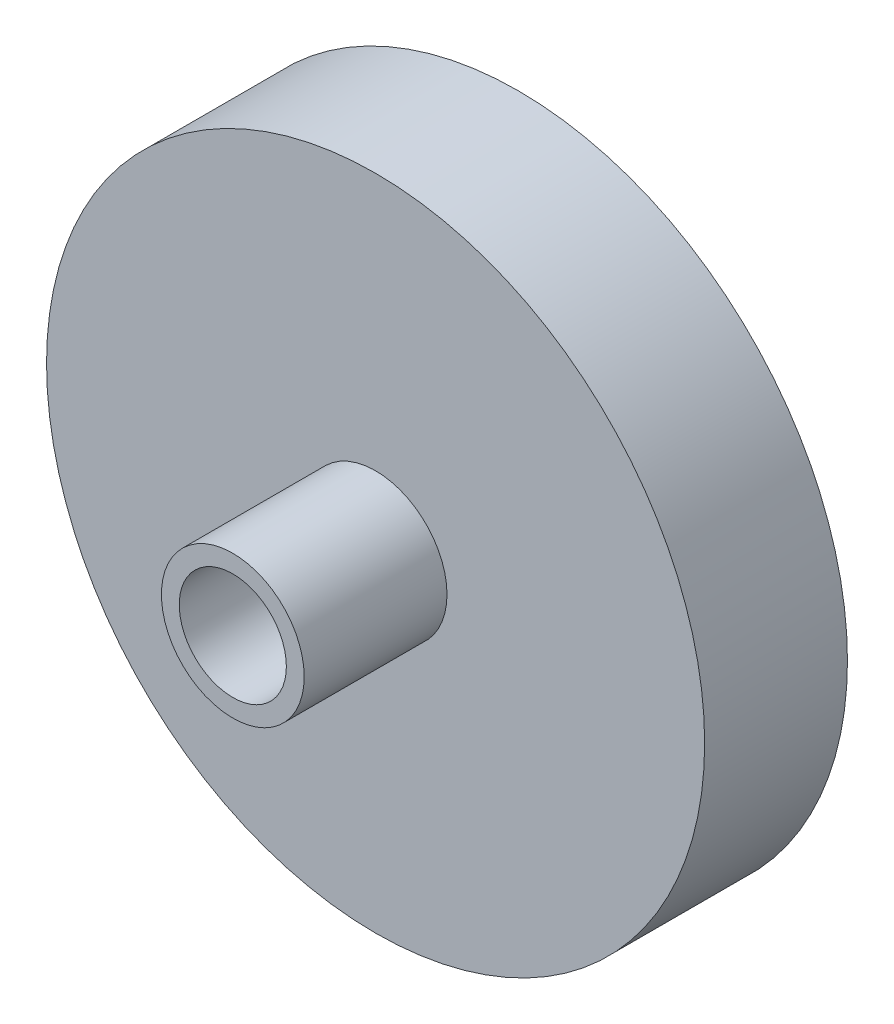
SolidWorks part; units mm, degrees
ref_plane "Plan de face" through (0, 0, 0) normal (0, 0, 1) x (1, 0, 0)
ref_plane "Plan de dessus" through (0, 0, 0) normal (0, 1, 0) x (1, 0, 0)
ref_plane "Plan de droite" through (0, 0, 0) normal (1, 0, 0) x (0, 0, -1)
sketch "Esquisse1" plane through (0, 0, 0) normal (0, 0, 1) x (1, 0, 0)
  circle A0 centre (0, 0) radius 46.0896
extrude "Boss.-Extru.1" add sketch "Esquisse1" along normal blind 20
sketch "Esquisse2" plane through (0, 0, 20) normal (0, 0, 1) x (1, 0, 0)
  circle A0 centre (0, 0) radius 10
  dimension "D1" = 20
extrude "Boss.-Extru.2" add sketch "Esquisse2" along normal blind 20
sketch "Esquisse3" plane through (0, 0, 40) normal (0, 0, 1) x (1, 0, 0)
  circle A0 centre (0, 0) radius 7.5
  dimension "D1" = 15
extrude "Enlèv. mat.-Extru.1" cut sketch "Esquisse3" against normal blind 20
